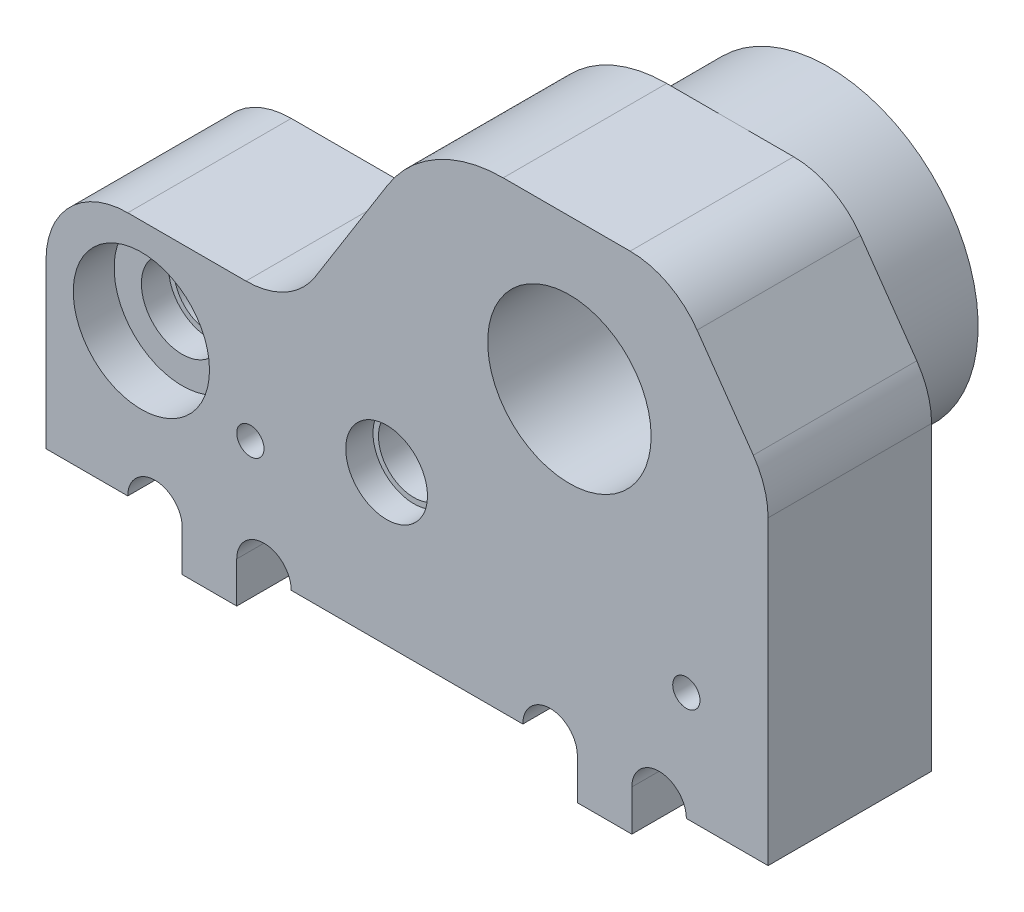
SolidWorks part; units mm, degrees
ref_plane "Front Plane" through (0, 0, 0) normal (0, 0, 1) x (1, 0, 0)
ref_plane "Top Plane" through (0, 0, 0) normal (0, 1, 0) x (1, 0, 0)
ref_plane "Right Plane" through (0, 0, 0) normal (1, 0, 0) x (0, 0, -1)
sketch "Sketch1" plane through (0, 0, 0) normal (0, 1, 0) x (1, 0, 0)
  line L1 (0, 0) -> (26.5, 0)
  line L2 (0, 0) -> (0, 6)
  line L3 (0, 6) -> (26.5, 6)
  line L4 (26.5, 0) -> (26.5, 6)
  dimension "D1" = 26.5
  dimension "D2" = 6
extrude "Boss-Extrude1" add sketch "Sketch1" along normal blind 17
ref_plane "Plane1" through (0, 5.5, 0) normal (0, 1, 0) x (1, 0, 0)
sketch "Sketch2" plane through (0, 0, 0) normal (0, 0, 1) x (1, 0, 0)
  line L0 (5.225, 5.5) -> (-5.225, 5.5) construction
  line L1 (26.5, 17) -> (26.5, 0) construction
  circle A0 centre (12.5, 5.5) radius 1.5
  circle A1 centre (12.5, 5.5) radius 9 construction
  dimension "D1" = 3
  dimension "D2" = 14
  dimension "D3" = 18
extrude "Cut-Extrude1" cut sketch "Sketch2" against normal blind 1
sketch "Sketch3" plane through (0, 0, -1) normal (0, 0, 1) x (1, 0, 0)
  circle A0 centre (12.5, 5.5) radius 1.3
  circle A1 centre (12.5, 5.5) radius 1.5 construction
  dimension "D1" = 0.2
extrude "Cut-Extrude2" cut sketch "Sketch3" against normal through all
sketch "Sketch4" plane through (0, 0, 0) normal (0, 0, 1) x (1, 0, 0)
  line L0 (3.3, 5.5) -> (-3.3, 5.5) construction
  circle A0 centre (19.2082, 11.5) radius 3
  circle A1 centre (12.5, 5.5) radius 1.5 construction
  dimension "D1" = 9
  dimension "D2" = 6
  dimension "D3" = 6
extrude "Cut-Extrude3" cut sketch "Sketch4" against normal through all
sketch "Sketch5" plane through (0, 0, 0) normal (0, 0, 1) x (1, 0, 0)
  line L0 (3.3, 5.5) -> (-3.3, 5.5) construction
  circle A0 centre (3.5, 5.5) radius 2.5
  circle A1 centre (12.5, 5.5) radius 1.5 construction
  dimension "D1" = 5
  dimension "D2" = 9
extrude "Cut-Extrude4" cut sketch "Sketch5" against normal blind 1.5
sketch "Sketch6" plane through (0, 0, -1.5) normal (0, 0, 1) x (1, 0, 0)
  circle A0 centre (3.5, 5.5) radius 1.5
  circle A1 centre (3.5, 5.5) radius 2.5 construction
  dimension "D1" = 3
extrude "Cut-Extrude8" cut sketch "Sketch6" against normal blind 1
sketch "Sketch7" plane through (0, 0, -2.5) normal (0, 0, 1) x (1, 0, 0)
  circle A0 centre (3.5, 5.5) radius 1.3
  circle A1 centre (3.5, 5.5) radius 1.5 construction
  dimension "D1" = 0.2
extrude "Cut-Extrude9" cut sketch "Sketch7" against normal through all
ref_plane "Plane2" through (0, 0, -9.3) normal (0, 0, -1) x (-1, 0, 0)
sketch "Sketch8" plane through (0, 0, -6) normal (0, 0, -1) x (-1, 0, 0)
  circle A0 centre (-3.5, 5.5) radius 2.5
  dimension "D1" = 5
extrude "Cut-Extrude10" cut sketch "Sketch8" against normal blind 1
sketch "Sketch9" plane through (0, 0, -5) normal (0, 0, -1) x (-1, 0, 0)
  circle A0 centre (-3.5, 5.5) radius 1.5
  dimension "D1" = 3
extrude "Cut-Extrude11" cut sketch "Sketch9" against normal blind 1
sketch "Sketch10" plane through (0, 0, -6) normal (0, 0, -1) x (-1, 0, 0)
  line L0 (-26.5, 17) -> (0, 17) construction
  circle A0 centre (-19.2082, 11.5) radius 5.5
  circle A1 centre (-19.2082, 11.5) radius 3 construction
  circle A2 centre (-19.2082, 11.5) radius 3
extrude "Boss-Extrude2" add sketch "Sketch10" along normal blind 3.5
sketch "Sketch11" plane through (0, 0, -6) normal (0, 0, -1) x (-1, 0, 0)
  circle A0 centre (-12.5, 5.5) radius 1.3 construction
  circle A1 centre (-12.5, 5.5) radius 1.3
  circle A2 centre (-12.5, 5.5) radius 3
  dimension "D1" = 6
extrude "Boss-Extrude4" add sketch "Sketch11" along normal blind 2
sketch "Sketch12" plane through (0, 0, -8) normal (0, 0, -1) x (-1, 0, 0)
  circle A0 centre (-12.5, 5.5) radius 1.5
  dimension "D1" = 3
extrude "Cut-Extrude12" cut sketch "Sketch12" against normal blind 1
sketch "Sketch17" plane through (0, 0, 0) normal (0, -1, 0) x (1, 0, 0)
  line L0 (10.175, 0) -> (-10.175, 0) construction
  line L1 (5, 0) -> (7, 0)
  line L2 (5, 0) -> (5, -6)
  line L3 (5, -6) -> (7, -6)
  line L4 (7, 0) -> (7, -6)
  line L5 (26.5, -6) -> (0, -6) construction
  line L6 (26.5, 0) -> (26.5, -6) construction
  line L7 (19.5, 0) -> (21.5, 0)
  line L8 (19.5, 0) -> (19.5, -6)
  line L9 (19.5, -6) -> (21.5, -6)
  line L10 (21.5, 0) -> (21.5, -6)
  line L11 (0, -5.236) -> (0, 5.236) construction
  dimension "D1" = 2
  dimension "D2" = 2
  dimension "D3" = 5
  dimension "D4" = 5
extrude "Boss-Extrude6" add sketch "Sketch17" along normal blind 1.5
sketch "Sketch18" plane through (0, 0, -6) normal (0, 0, -1) x (-1, 0, 0)
  line L0 (3.3, 0) -> (-3.3, 0) construction
  line L1 (-21.5, -1.5) -> (-21.5, 0) construction
  line L2 (-19.5, -1.5) -> (-19.5, 0) construction
  line L3 (-7, -1.5) -> (-7, 0) construction
  line L4 (-5, -1.5) -> (-5, 0) construction
  circle A0 centre (-22.5, 0) radius 1
  circle A1 centre (-18.5, 0) radius 1
  circle A2 centre (-8, 0) radius 1
  circle A3 centre (-4, 0) radius 1
  dimension "D1" = 2
extrude "Cut-Extrude17" cut sketch "Sketch18" against normal through all
chamfer "Chamfer2" distance 5 distance2 3.5 1 edges at (26.5, 17, -3)
fillet "Fillet11" radius 3 2 edges at (26.5, 12, -3) (23, 17, -3)
sketch "Sketch19" plane through (0, 0, -6) normal (0, 0, -1) x (-1, 0, 0)
  line L0 (-14.5471, 14.4196) -> (-9.9576, 7.0925)
  line L1 (-13.8002, 2.7964) -> (-21.5918, 6.5434)
  circle A0 centre (-12.5, 5.5) radius 3 construction
  circle A1 centre (-19.2082, 11.5) radius 5.5 construction
  arc A2 (-9.9576, 7.0925) -> (-13.8002, 2.7964) centre (-12.5, 5.5) ccw
  arc A3 (-21.5918, 6.5434) -> (-14.5471, 14.4196) centre (-19.2082, 11.5) ccw
extrude "Boss-Extrude7" add sketch "Sketch19" along normal up to surface (2 mm away) up to face at (11, 5.5, -8)
sketch "Sketch20" plane through (0, 0, -6) normal (0, 0, -1) x (-1, 0, 0)
  line L0 (3.3, 0) -> (-3.3, 0) construction
  line L1 (0, 17) -> (-14.011, 17)
  line L2 (0, 17) -> (0, 9)
  line L3 (0, 9) -> (-9, 9)
  line L5 (-9, 9) -> (-14.011, 17)
  line L6 (-19.2082, 17) -> (0, 17) construction
  line L7 (-9.9576, 7.0925) -> (-14.5471, 14.4196) construction
  dimension "D1" = 9
extrude "Cut-Extrude19" cut sketch "Sketch20" against normal through all
fillet "Fillet13" radius 5 1 edges at (14.011, 17, -3)
fillet "Fillet14" radius 3 1 edges at (9, 9, -3)
fillet "Fillet15" radius 3 1 edges at (0, 9, -3)
sketch "Skizze1" plane through (0, 0, -6) normal (0, 0, -1) x (-1, 0, 0)
  line L0 (3.3, 0) -> (-3.3, 0) construction
  line L1 (-26.5, 11.0543) -> (-26.5, 0) construction
  circle A0 centre (-23.5, 4) radius 0.5
  circle A1 centre (-7.5, 4) radius 0.5
  dimension "D1" = 1
  dimension "D2" = 1
  dimension "D3" = 4
  dimension "D4" = 16
  dimension "D5" = 3
extrude "Schnitt-Linear austragen1" cut sketch "Skizze1" against normal through all
